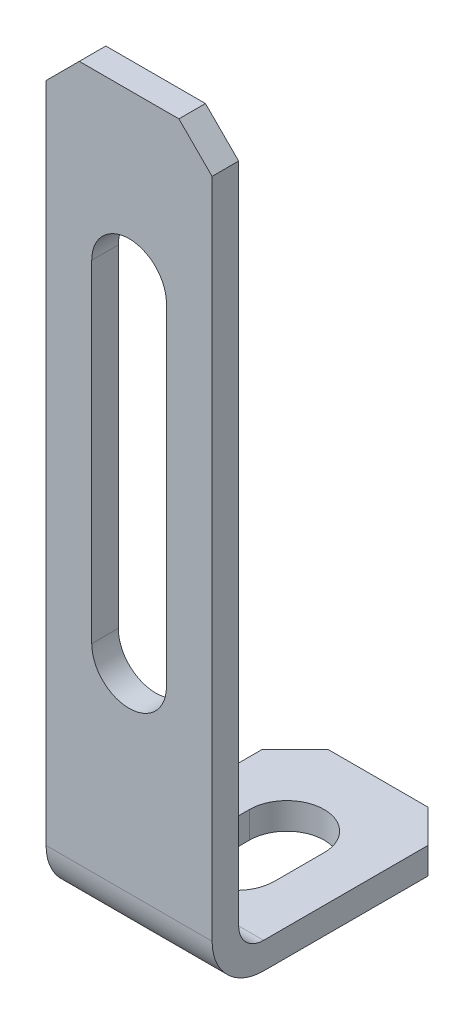
SolidWorks part; units mm, degrees
ref_plane "Front Plane" through (0, 0, 0) normal (0, 0, 1) x (1, 0, 0)
ref_plane "Top Plane" through (0, 0, 0) normal (0, 1, 0) x (1, 0, 0)
ref_plane "Right Plane" through (0, 0, 0) normal (1, 0, 0) x (0, 0, -1)
ref_plane "Plane1" through (10, 0, 0) normal (1, 0, 0) x (0, 0, -1)
sketch "Sketch1" plane through (10, 0, 0) normal (1, 0, 0) x (0, 0, -1)
  line L0 (0, 45) -> (0, 0)
  line L1 (0, 0) -> (15, 0)
  line L2 (15, 0) -> (15, 45)
  line L3 (15, 45) -> (0, 45)
extrude "Boss-Extrude1" add sketch "Sketch1" against normal blind 10
sketch "Sketch2" plane through (0, 0, 0) normal (-1, 0, 0) x (0, 0, 1)
  line L0 (-15, 1.6) -> (-1.6, 1.6)
  line L1 (-1.6, 1.6) -> (-1.6, 45)
  line L2 (-1.6, 45) -> (-15, 45)
  line L3 (-15, 45) -> (-15, 1.6)
extrude "Cut-Extrude1" cut sketch "Sketch2" against normal through all
sketch "Sketch3" plane through (0, 1.6, 0) normal (0, 1, 0) x (-1, 0, 0)
  line L0 (-2.75, -9.5) -> (-2.75, -6.5)
  line L1 (-7.25, -6.5) -> (-7.25, -9.5)
  arc A0 (-7.25, -9.5) -> (-2.75, -9.5) centre (-5, -9.5) ccw
  arc A1 (-2.75, -6.5) -> (-7.25, -6.5) centre (-5, -6.5) ccw
extrude "Cut-Extrude2" cut sketch "Sketch3" against normal through all
sketch "Sketch4" plane through (0, 0, 0) normal (0, 0, 1) x (1, 0, 0)
  line L0 (7.25, 15) -> (7.25, 35)
  line L1 (2.75, 35) -> (2.75, 15)
  arc A0 (2.75, 15) -> (7.25, 15) centre (5, 15) ccw
  arc A1 (7.25, 35) -> (2.75, 35) centre (5, 35) ccw
extrude "Cut-Extrude3" cut sketch "Sketch4" against normal through all
chamfer "Chamfer1" distance 2 angle 45 4 edges at (0, 45, -0.8) (0, 0.8, -15) (10, 0.8, -15) (10, 45, -0.8)
fillet "Fillet1" radius 1.5 1 edges at (5, 1.6, -1.6)
fillet "Fillet2" radius 3.1 1 edges at (5, 0, 0)
